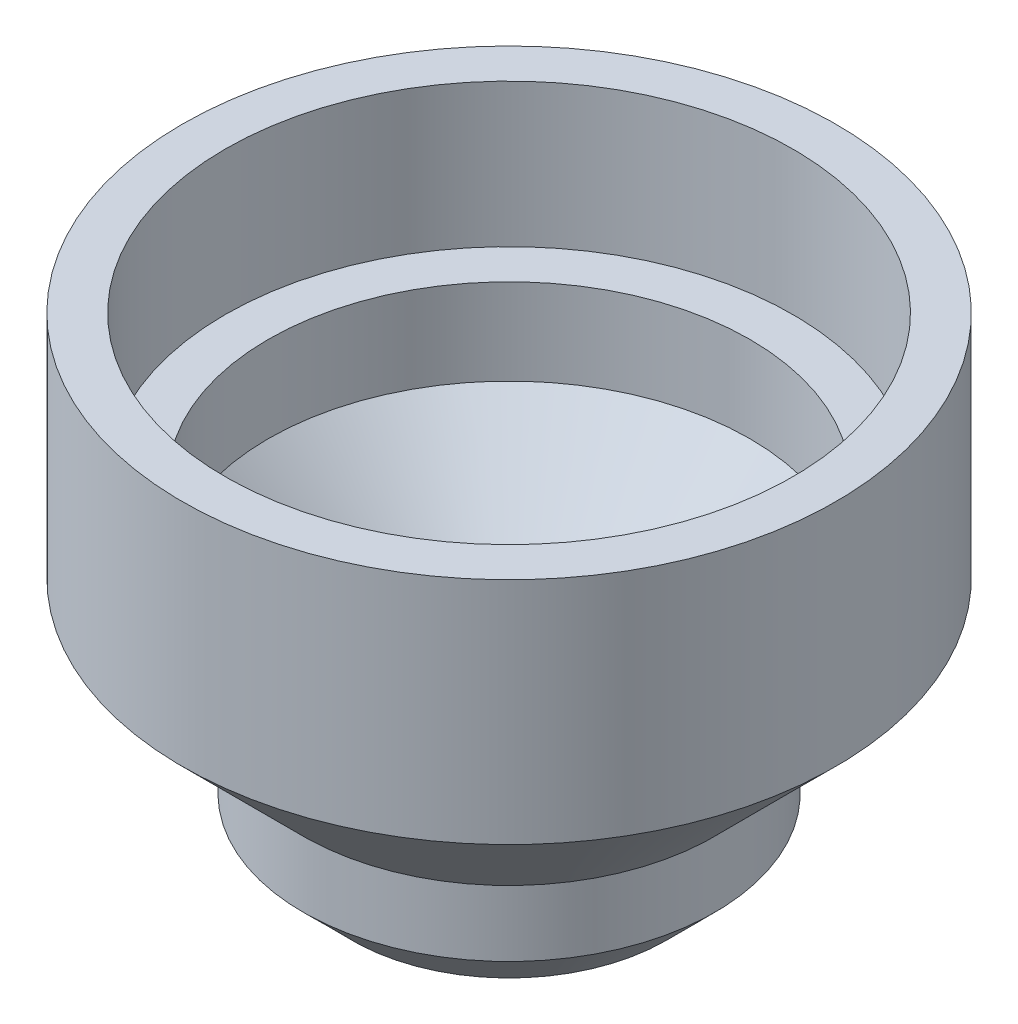
SolidWorks part; units mm, degrees
ref_plane "Płaszczyzna przednia" through (0, 0, 0) normal (0, 0, 1) x (1, 0, 0)
ref_plane "Płaszczyzna górna" through (0, 0, 0) normal (0, 1, 0) x (1, 0, 0)
ref_plane "Płaszczyzna prawa" through (0, 0, 0) normal (1, 0, 0) x (0, 0, -1)
sketch "Sketch1" plane through (0, 0, 0) normal (0, 0, 1) x (1, 0, 0)
  line L0 (-11.4, 0) -> (11.4, 0) construction
  line L1 (-7.4, -4) -> (7.4, -4) construction
  line L2 (-11.4, 0) -> (-7.4, -4) construction
  line L3 (11.4, 0) -> (7.4, -4) construction
  line L4 (0, 51.2742) -> (0, -55.0085) construction
  line L6 (7.4, -4) -> (11.4, 0)
  line L7 (7.4, -1) -> (11.4, 3)
  line L8 (7.4, -1) -> (7.4, -4)
  line L12 (11.4, 0) -> (11.4, 8)
  line L13 (8.4, 8) -> (8.4, 0)
  line L14 (8.4, 8) -> (11.4, 8)
  line L15 (-29.798, -4) -> (34.28, -4) construction
  line L16 (8.4, 3) -> (9.9, 3)
  line L17 (9.9, 8) -> (9.9, 3)
  line L30 (7.4, -4) -> (5.4803, -5.9197)
  line L31 (7.4, -1) -> (5.4803, -2.9197)
  line L32 (5.4803, -2.9197) -> (5.4803, -5.9197)
  line L33 (5.4803, -5.9197) -> (5.4803, -8.2153)
  line L34 (5.4803, -8.2153) -> (7.1803, -6.5153)
  line L35 (7.1803, -4.2197) -> (7.1803, -6.5153)
  point P3 (0, 0)
  dimension "D1" = 22.8
  dimension "D2" = 14.8
  dimension "D3" = 4
  dimension "D4" = 8
  dimension "D5" = 3
  dimension "D6" = 3
  dimension "D7" = 1.5
  dimension "D9" = 1.7
  dimension "D8" = 5
revolve "Revolve1" add sketch "Sketch1" angle 360 about L4
